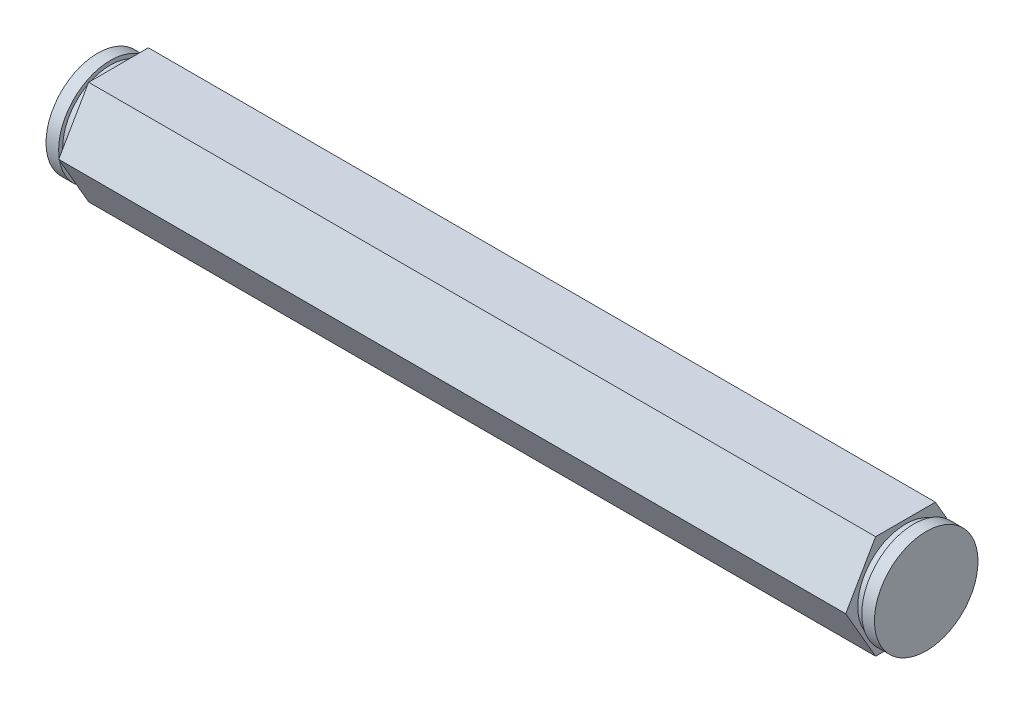
SolidWorks part; units mm, degrees
material "7075-T6 (SN)"
ref_plane "Front Plane" through (0, 0, 0) normal (0, 0, 1) x (1, 0, 0)
ref_plane "Top Plane" through (0, 0, 0) normal (0, 1, 0) x (1, 0, 0)
ref_plane "Right Plane" through (0, 0, 0) normal (1, 0, 0) x (0, 0, -1)
sketch "Sketch1" plane through (0, 0, 0) normal (1, 0, 0) x (0, 0, -1)
  line L1 (7.3323, 0) -> (3.6662, 6.35)
  line L2 (3.6662, 6.35) -> (-3.6662, 6.35)
  line L3 (-3.6662, 6.35) -> (-7.3323, 0)
  line L4 (-7.3323, 0) -> (-3.6662, -6.35)
  line L5 (-3.6662, -6.35) -> (3.6662, -6.35)
  line L6 (3.6662, -6.35) -> (7.3323, 0)
  circle A0 centre (0, 0) radius 6.35 construction
  dimension "D1" = 12.7
extrude "Boss-Extrude1" add sketch "Sketch1" along normal mid plane 101.6
sketch "Sketch2" plane through (0, 0, 0) normal (0, 1, 0) x (1, 0, 0)
  line L0 (48.26, -5.8547) -> (49.2506, -5.8547)
  line L1 (49.2506, -5.8547) -> (49.2506, -6.35)
  line L2 (49.2506, -6.35) -> (50.8, -6.35)
  line L3 (50.8, -6.35) -> (50.8, -8.89)
  line L4 (50.8, -8.89) -> (48.26, -8.89)
  line L5 (48.26, -8.89) -> (48.26, -5.8547)
  line L6 (0, 0) -> (49.5443, 0) construction
  dimension "D1" = 2.54
  dimension "D2" = 6.35
  dimension "D3" = 5.8547
  dimension "D4" = 2.54
  dimension "D5" = 0.9906
revolve "Cut-Revolve1" cut sketch "Sketch2" angle 360 about L6
mirror "Mirror1" about plane through (0, 0, 0) normal (1, 0, 0) of "Cut-Revolve1"
